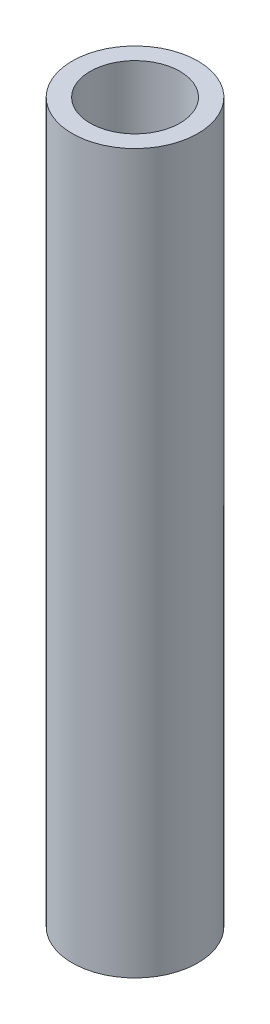
SolidWorks part; units mm, degrees
ref_plane "Front Plane" through (0, 0, 0) normal (0, 0, 1) x (1, 0, 0)
ref_plane "Top Plane" through (0, 0, 0) normal (0, 1, 0) x (1, 0, 0)
ref_plane "Right Plane" through (0, 0, 0) normal (1, 0, 0) x (0, 0, -1)
sketch "Sketch1" plane through (0, 0, 0) normal (0, 1, 0) x (1, 0, 0)
  circle A0 centre (0, 0) radius 13.335
  circle A1 centre (0, 0) radius 9.525
  dimension "D1" = 26.67
  dimension "D2" = 19.05
extrude "Boss-Extrude1" add sketch "Sketch1" along normal blind 152.4
